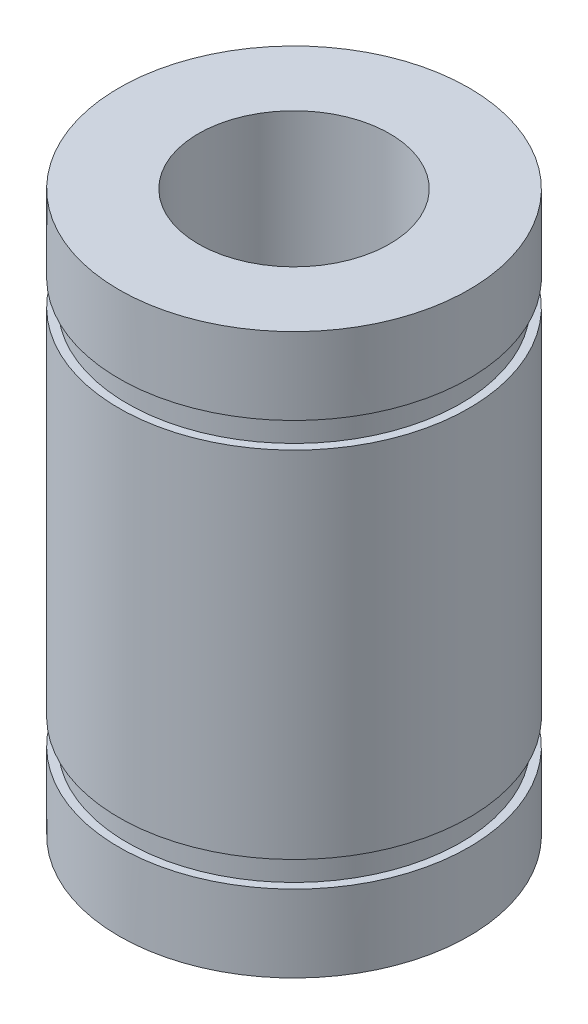
SolidWorks part; units mm, degrees
ref_plane "Alzado" through (0, 0, 0) normal (0, 0, 1) x (1, 0, 0)
ref_plane "Planta" through (0, 0, 0) normal (0, 1, 0) x (1, 0, 0)
ref_plane "Vista lateral" through (0, 0, 0) normal (1, 0, 0) x (0, 0, -1)
sketch "Croquis1" plane through (0, 0, 0) normal (0, 1, 0) x (1, 0, 0)
  circle A0 centre (0, 0) radius 7.5
  circle A1 centre (0, 0) radius 4.1
  dimension "D1" = 8.2
  dimension "D2" = 15
extrude "Saliente-Extruir1" add sketch "Croquis1" along normal blind 24
sketch "Croquis2" plane through (0, 0, 0) normal (0, 0, 1) x (1, 0, 0)
  line L0 (-7.5, 24) -> (-7.5, 0) construction
  line L1 (-7.5, 19.6) -> (-7.15, 19.6)
  line L2 (-7.5, 20.7) -> (-7.5, 19.6)
  line L3 (-7.5, 4.4) -> (-7.15, 4.4)
  line L4 (-7.15, 20.7) -> (-7.15, 19.6)
  line L5 (0, 0) -> (0, 24) construction
  line L6 (4.1, 24) -> (-4.1, 24) construction
  line L7 (0, 12) -> (-7.15, 12) construction
  line L8 (-7.5, 3.3) -> (-7.5, 4.4)
  line L9 (-7.15, 3.3) -> (-7.15, 4.4)
  line L11 (-7.5, 20.7) -> (-7.15, 20.7)
  line L15 (-7.5, 3.3) -> (-7.15, 3.3)
  dimension "D1" = 15.2
  dimension "D2" = 14.3
  dimension "D3" = 1.1
revolve "Cortar-Revolución1" cut sketch "Croquis2" angle 360 about L5
